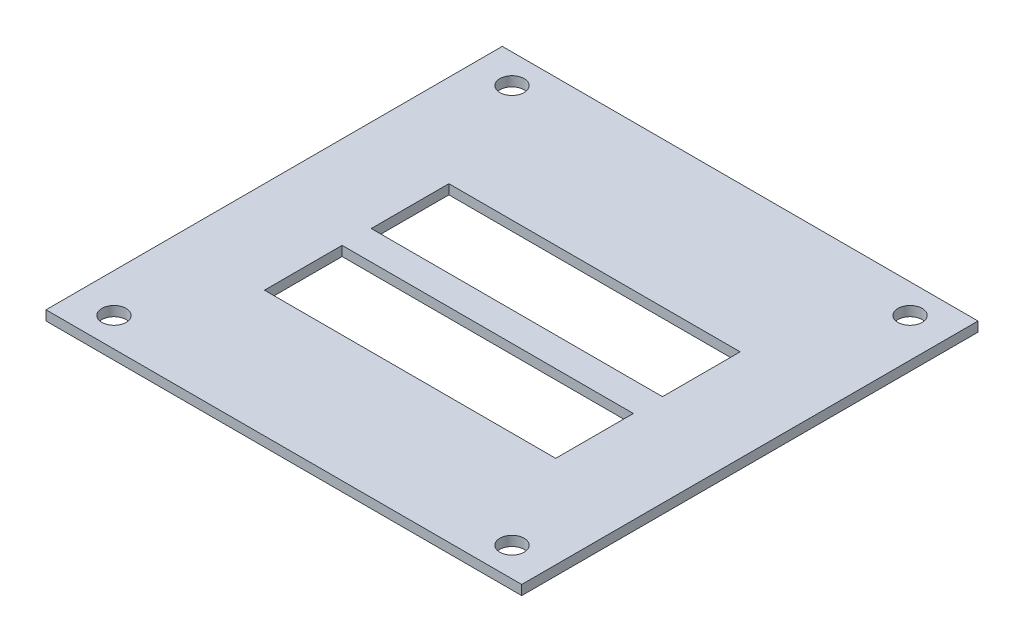
SolidWorks part; units mm, degrees
ref_plane "Alzado" through (0, 0, 0) normal (0, 0, 1) x (1, 0, 0)
ref_plane "Planta" through (0, 0, 0) normal (0, 1, 0) x (1, 0, 0)
ref_plane "Vista lateral" through (0, 0, 0) normal (1, 0, 0) x (0, 0, -1)
sketch "Croquis1" plane through (0, 0, 0) normal (0, 1, 0) x (1, 0, 0)
  line L1 (0, 47) -> (49, 47)
  line L2 (0, 47) -> (0, 0)
  line L3 (0, 0) -> (49, 0)
  line L4 (49, 47) -> (49, 0)
  dimension "D1" = 49
  dimension "D2" = 47
extrude "Saliente-Extruir1" add sketch "Croquis1" along normal blind 1
sketch "Croquis2" plane through (0, 1, 0) normal (0, 1, 0) x (1, 0, 0)
  line L0 (4, 47) -> (4, 0) construction
  line L1 (49, 47) -> (0, 47) construction
  line L2 (0, 0) -> (49, 0) construction
  line L3 (45, 47) -> (45, 0) construction
  line L4 (0, 44) -> (49, 44) construction
  line L5 (0, 47) -> (0, 0) construction
  line L6 (49, 0) -> (49, 47) construction
  line L7 (0, 3) -> (49, 3) construction
  dimension "D1" = 4
  dimension "D2" = 4
  dimension "D3" = 3
  dimension "D4" = 3
hole_wizard "Perforador para roscar para macho de roscar para M31" positions "Croquis3D2" profile "Croquis4" hole size "M3" standard "ISO" end condition up to next
sketch3d "Croquis3D2"
  line L0 (4, 1, -47) -> (4, 1, 0) construction
  line L1 (0, 1, -44) -> (49, 1, -44) construction
  line L2 (0, 1, -3) -> (49, 1, -3) construction
  line L3 (45, 1, -47) -> (45, 1, 0) construction
  point P0 (4, 1, -44)
  point P6 (4, 1, -3)
  point P10 (45, 1, -3)
  point P14 (45, 1, -44)
sketch "Croquis4" plane through (4, 1, -44) normal (1, 0, 0) x (0, 0, 1)
  line L0 (0, 0) -> (0, 1)
  line L1 (0, 1) -> (1.25, 1)
  line L2 (1.25, 1) -> (1.25, 0)
  line L5 (1.25, 0) -> (0, 0)
  line L11 (0, -6.35) -> (0, 107.95) construction
  dimension "Diámetro de taladro hasta el siguiente" = 2.5
  dimension "Profundidad de taladro hasta el siguiente" = 1
sketch "Croquis5" plane through (0, 1, 0) normal (0, 1, 0) x (1, 0, 0)
  line L0 (49, 23.5) -> (0, 23.5) construction
  line L3 (49, 0) -> (49, 47) construction
  line L4 (0, 47) -> (0, 0) construction
  line L5 (49, 22.5) -> (0, 22.5) construction
  line L6 (24.5, 0) -> (24.5, 47) construction
  line L7 (39.5, 13) -> (9.5, 13)
  line L8 (39.5, 13) -> (39.5, 21)
  line L9 (39.5, 21) -> (9.5, 21)
  line L10 (9.5, 13) -> (9.5, 21)
  line L11 (0, 0) -> (49, 0) construction
  line L12 (49, 47) -> (0, 47) construction
  line L13 (39.5, 24) -> (9.5, 24)
  line L14 (9.5, 32) -> (9.5, 24)
  line L15 (39.5, 32) -> (9.5, 32)
  line L16 (39.5, 32) -> (39.5, 24)
  dimension "D1" = 1
  dimension "D2" = 30
  dimension "D3" = 15
  dimension "D4" = 1.5
  dimension "D5" = 8
extrude "Cortar-Extruir1" cut sketch "Croquis5" against normal up to next
